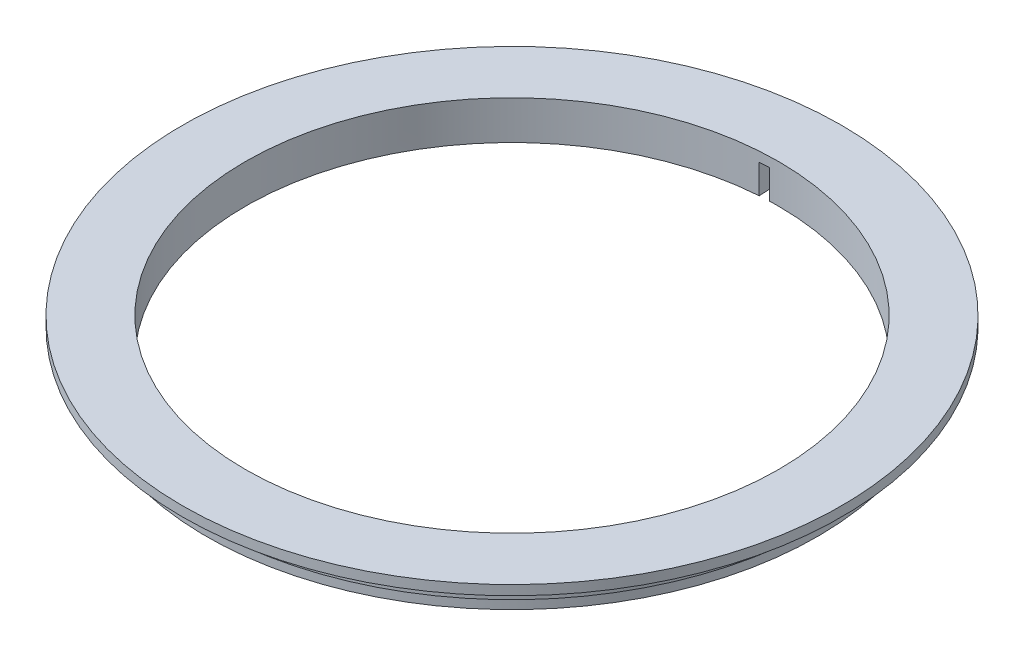
SolidWorks part; units mm, degrees
ref_plane "Plan de face" through (0, 0, 0) normal (0, 0, 1) x (1, 0, 0)
ref_plane "Plan de dessus" through (0, 0, 0) normal (0, 1, 0) x (1, 0, 0)
ref_plane "Plan de droite" through (0, 0, 0) normal (1, 0, 0) x (0, 0, -1)
sketch "Esquisse1" plane through (0, 0, 0) normal (0, 0, 1) x (1, 0, 0)
  line L0 (157.568, 0) -> (157.568, 5)
  line L1 (137.568, 0) -> (157.568, 0)
  line L2 (0, 0) -> (0, 35) construction
  line L3 (137.568, 20) -> (170, 20)
  line L4 (157.568, 5) -> (158.3638, 5)
  line L5 (158.3638, 5) -> (158.3638, 10)
  line L6 (158.3638, 10) -> (159.1596, 10)
  line L7 (159.1596, 10) -> (159.1596, 15)
  line L8 (170, 20) -> (170, 15)
  line L9 (170, 15) -> (159.1596, 15)
  line L10 (137.568, 20) -> (137.568, 0)
  point P0 (0, 0)
  dimension "D1" = 157.568
  dimension "D2" = 5
  dimension "D3" = 5
  dimension "D4" = 5
  dimension "D5" = 0.7958
  dimension "D6" = 0.7958
  dimension "D7" = 170
  dimension "D8" = 5
  dimension "D9" = 20
revolve "Révolution1" add sketch "Esquisse1" angle 360 about L2
sketch "Esquisse2" plane through (0, 15, 0) normal (0, -1, 0) x (1, 0, 0)
  line L0 (-2.5, -160.1549) -> (-2.5, -161.1549)
  line L1 (-2.5, -161.1549) -> (-2.5, -159.1549) construction
  line L2 (-14.2544, -159.5389) -> (-14.359, -160.5334)
  line L3 (-14.359, -160.5334) -> (-14.1499, -158.5444) construction
  line L4 (-9.6935, -184.9626) -> (-6.7838, -129.4425) construction
  line L5 (-9.4069, -131.7267) -> (-11.5515, -172.647)
  line L6 (-9.4069, -131.7267) -> (-4.4138, -131.9884)
  line L7 (-11.5515, -172.647) -> (-6.5583, -172.9087)
  line L8 (-4.4138, -131.9884) -> (-6.5583, -172.9087)
  dimension "D1" = 5
extrude "Enlèv. mat.-Extru.1" cut sketch "Esquisse2" along normal blind 20.3957 contours L7 L8 L6 L5
equation "\"D3@Esquisse1\"=\"D2@Esquisse1\""
equation "\"D4@Esquisse1\"=\"D2@Esquisse1\""
equation "\"D6@Esquisse1\"=\"D5@Esquisse1\""
